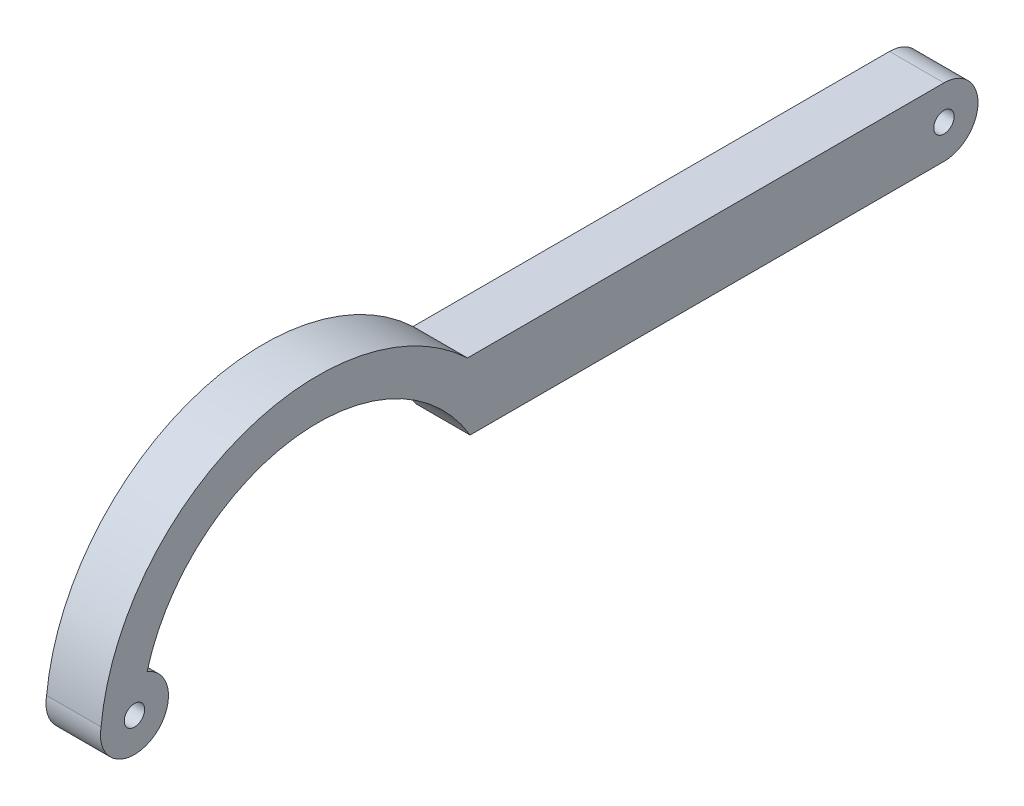
SolidWorks part; units mm, degrees
ref_plane "Front Plane" through (0, 0, 0) normal (0, 0, 1) x (1, 0, 0)
ref_plane "Top Plane" through (0, 0, 0) normal (0, 1, 0) x (1, 0, 0)
ref_plane "Right Plane" through (0, 0, 0) normal (1, 0, 0) x (0, 0, -1)
sketch "Sketch1" plane through (0, 0, 0) normal (1, 0, 0) x (0, 0, -1)
  line L0 (0, 0) -> (59.4643, 8) construction
  line L2 (59.4643, 10.5) -> (24.4643, 10.5)
  line L4 (59.4643, 5.5) -> (24.654, 5.5)
  arc A0 (-2.4531, 0.4822) -> (0.9302, 2.3205) centre (0, 0) ccw
  arc A1 (59.4643, 5.5) -> (59.4643, 10.5) centre (59.4643, 8) ccw
  circle A4 centre (0, 0) radius 2.5 construction
  circle A5 centre (59.4643, 8) radius 0.75
  arc A6 (0.9302, 2.3205) -> (24.654, 5.5) centre (13.4664, -1.121) cw
  arc A7 (24.4643, 10.5) -> (-2.4531, 0.4822) centre (13.4664, -1.121) ccw
  circle A8 centre (0, 0) radius 0.75
  dimension "D1" = 60
  dimension "D2" = 1.5
  dimension "D5" = 5
  dimension "D6" = 1.5
  dimension "D9" = 13
  dimension "D10" = 3
  dimension "D3" = 8
  dimension "D7" = 35
extrude "Boss-Extrude1" add sketch "Sketch1" along normal blind 4
sketch "Sketch2" plane through (4, 0, 0) normal (1, 0, 0) x (0, 0, -1)
